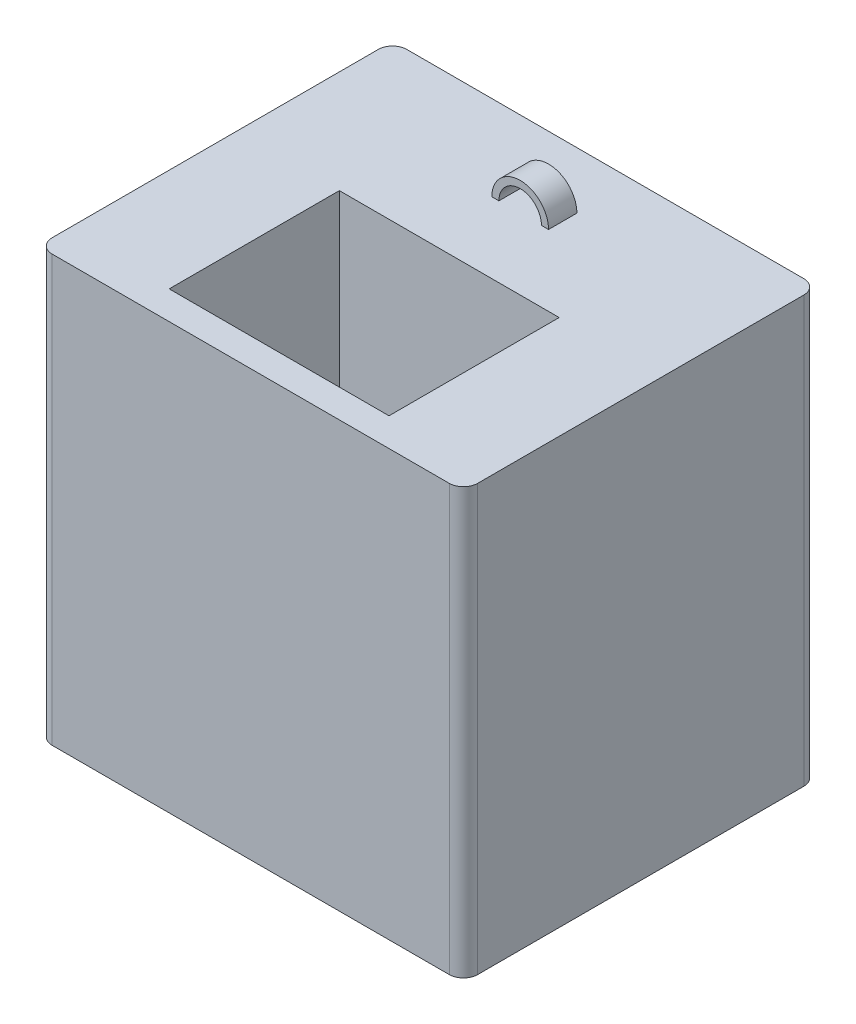
SolidWorks part; units mm, degrees
ref_plane "Front Plane" through (0, 0, 0) normal (0, 0, 1) x (1, 0, 0)
ref_plane "Top Plane" through (0, 0, 0) normal (0, 1, 0) x (1, 0, 0)
ref_plane "Right Plane" through (0, 0, 0) normal (1, 0, 0) x (0, 0, -1)
sketch "Sketch1" plane through (0, 0, 0) normal (0, 1, 0) x (1, 0, 0)
  line L1 (-15, 12.5) -> (15, 12.5)
  line L2 (-15, 12.5) -> (-15, -12.5)
  line L3 (-15, -12.5) -> (15, -12.5)
  line L4 (15, 12.5) -> (15, -12.5)
  line L5 (-15, 12.5) -> (15, -12.5) construction
  line L6 (-15, -12.5) -> (15, 12.5) construction
  point P0 (0, 0)
  dimension "D1" = 30
  dimension "D2" = 25
extrude "Boss-Extrude1" add sketch "Sketch1" along normal blind 30
sketch "Sketch2" plane through (0, 30, 0) normal (0, 1, 0) x (1, 0, 0)
  line L0 (0, 12.5) -> (0, -12.5) construction
  line L1 (15, 12.5) -> (-15, 12.5) construction
  line L2 (-15, -12.5) -> (15, -12.5) construction
  line L4 (-7.75, 1.5) -> (7.75, 1.5)
  line L5 (-7.75, 1.5) -> (-7.75, -10.5)
  line L6 (-7.75, -10.5) -> (7.75, -10.5)
  line L7 (7.75, 1.5) -> (7.75, -10.5)
  line L8 (-7.75, 1.5) -> (7.75, -10.5) construction
  line L9 (-7.75, -10.5) -> (7.75, 1.5) construction
  point P6 (0, -4.5)
  dimension "D1" = 15.5
  dimension "D2" = 12
  dimension "D3" = 2
extrude "Cut-Extrude1" cut sketch "Sketch2" against normal blind 30
fillet "Fillet1" radius 1 4 edges at (-15, 15, -12.5) (-15, 15, 12.5) (15, 15, -12.5) (15, 15, 12.5)
ref_plane "Plane1" through (0, 0, -7.5) normal (0, 0, -1) x (-1, 0, 0)
sketch "Sketch3" plane through (0, 0, -7.5) normal (0, 0, -1) x (-1, 0, 0)
  line L0 (0, 30) -> (0, 0) construction
  line L1 (-14, 30) -> (14, 30) construction
  line L2 (-2, 30) -> (2, 30)
  arc A0 (2, 30) -> (-2, 30) centre (0, 30) ccw
  arc A1 (1.5, 30) -> (-1.5, 30) centre (0, 30) ccw
  circle A3 centre (0, 30) radius 2 construction
  circle A4 centre (0, 30) radius 1.5 construction
  point P5 (1.75, 30)
  point P10 (1.9126, 30.5847)
  dimension "D1" = 4
  dimension "D2" = 0.5
extrude "Boss-Extrude2" add sketch "Sketch3" along normal mid plane 2 contours A1 L2 A0
